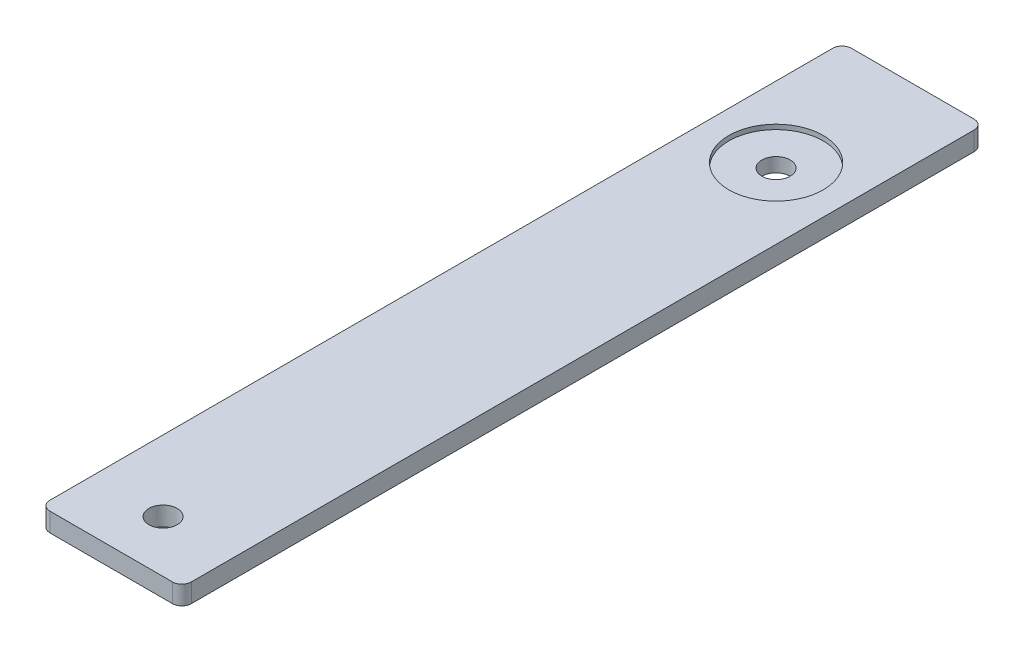
SolidWorks part; units mm, degrees
ref_plane "Front Plane" through (0, 0, 0) normal (0, 0, 1) x (1, 0, 0)
ref_plane "Top Plane" through (0, 0, 0) normal (0, 1, 0) x (1, 0, 0)
ref_plane "Right Plane" through (0, 0, 0) normal (1, 0, 0) x (0, 0, -1)
sketch "Sketch1" plane through (0, 0, 0) normal (0, 1, 0) x (1, 0, 0)
  line L1 (0, 0) -> (15, 0)
  line L2 (0, 0) -> (0, 85)
  line L3 (0, 85) -> (15, 85)
  line L4 (15, 0) -> (15, 85)
  circle A1 centre (7.5, 70.5) radius 1.5
  circle A2 centre (7.5, 5.5) radius 1.5
  dimension "D3" = 5.5
  dimension "D1" = 15
  dimension "D2" = 85
  dimension "D5" = 14.5
  dimension "D6" = 79.5
extrude "Boss-Extrude1" add sketch "Sketch1" along normal blind 2
sketch "Sketch2" plane through (0, 2, 0) normal (0, 1, 0) x (1, 0, 0)
  circle A0 centre (7.5, 70.5) radius 5
extrude "Cut-Extrude1" cut sketch "Sketch2" against normal blind 0.5
fillet "Fillet1" radius 1 4 edges at (0, 1, 0) (15, 1, 0) (15, 1, -85) (0, 1, -85)
